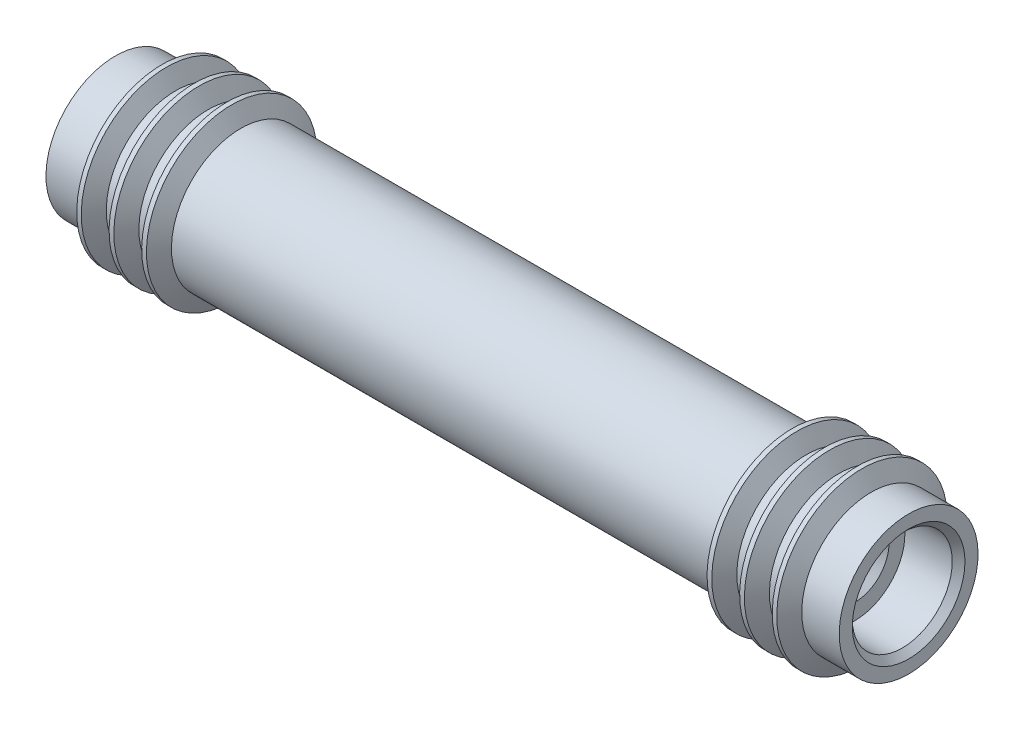
SolidWorks part; units mm, degrees
ref_plane "Front Plane" through (0, 0, 0) normal (0, 0, 1) x (1, 0, 0)
ref_plane "Top Plane" through (0, 0, 0) normal (0, 1, 0) x (1, 0, 0)
ref_plane "Right Plane" through (0, 0, 0) normal (1, 0, 0) x (0, 0, -1)
sketch "Sketch2" plane through (0, 0, 0) normal (0, 0, 1) x (1, 0, 0)
  line L0 (0, 0) -> (0, 28.4375) construction
  line L1 (-31.75, 4) -> (-27.45, 4) construction
  line L2 (-31.75, 4) -> (-31.75, -4) construction
  line L3 (-31.75, -4) -> (-27.45, -4) construction
  line L4 (-27.45, 4) -> (-27.45, -4) construction
  line L5 (-31.75, 4) -> (-27.45, -4) construction
  line L6 (-31.75, -4) -> (-27.45, 4) construction
  line L7 (27.45, 4.5) -> (36.1332, 4.5) construction
  line L8 (27.45, 4.5) -> (27.45, -4.5) construction
  line L9 (27.45, -4.5) -> (36.1332, -4.5) construction
  line L10 (36.1332, 4.5) -> (36.1332, -4.5) construction
  line L11 (27.45, 4.5) -> (36.1332, -4.5) construction
  line L12 (27.45, -4.5) -> (36.1332, 4.5) construction
  line L13 (-31.75, 0) -> (36.1332, 0) construction
  line L14 (-31.75, 5.5562) -> (-28.75, 5.5562)
  line L15 (-28.75, 5.5562) -> (-28.0168, 6.8262)
  line L16 (-28.0168, 6.8262) -> (-27.6572, 6.8262)
  line L19 (-25.4288, 6.8262) -> (-25.0478, 6.8263)
  line L20 (-25.0478, 6.8263) -> (-24.3145, 5.5562)
  line L21 (-20.3302, 3.175) -> (0, 3.175) construction
  line L22 (-31.75, 5.5562) -> (-31.75, 4)
  line L23 (-31.75, 4) -> (-27.45, 4)
  line L24 (-27.45, 4) -> (-27.45, 0)
  line L25 (-27.45, 0) -> (0, 0)
  line L26 (0, 0) -> (0, 3.175)
  line L27 (-33.2419, -5.5563) -> (-33.2419, 5.5562) construction
  line L28 (-26.543, 5.5562) -> (-26.543, 7.68) construction
  line L29 (-26.543, 5.5562) -> (26.543, 5.5562) construction
  line L30 (-31.75, 5.5562) -> (31.75, 5.5562) construction
  line L31 (0, 1.6) -> (-12.5, 1.6) construction
  line L32 (-12.5, 1.6) -> (-14.1, 0) construction
  line L33 (-12.5, 1.6) -> (-12.5, -1.6) construction
  line L34 (-12.5, 1.6) -> (12.5, 1.6) construction
  line L35 (-27.45, 1.7145) -> (-21.925, 1.7145)
  line L36 (-21.925, 1.7145) -> (-21.925, 0)
  line L37 (-27.45, 2.73) -> (-26.942, 2.222)
  line L38 (-21.925, 1.7145) -> (-34.925, 1.7145) construction
  line L39 (-21.925, 1.7145) -> (-21.925, -1.7145) construction
  line L40 (-21.925, -1.7145) -> (-34.925, -1.7145) construction
  line L41 (-34.925, 1.7145) -> (-34.925, -1.7145) construction
  line L42 (-26.942, 2.222) -> (-26.942, 0)
  line L43 (-26.924, 5.5562) -> (-26.162, 5.5562)
  line L44 (-27.6572, 6.8262) -> (-26.924, 5.5562)
  line L45 (-25.4288, 6.8262) -> (-26.162, 5.5562)
  line L46 (-24.3145, 5.5562) -> (-23.5525, 5.5562)
  line L47 (-23.5525, 5.5562) -> (-22.8193, 6.8263)
  line L48 (-22.8193, 6.8263) -> (-22.4383, 6.8263)
  line L49 (-22.4383, 6.8263) -> (-21.7051, 5.5562)
  line L50 (-24.3145, 5.5562) -> (-22.9397, 3.175) construction
  line L51 (-23.9335, 5.5562) -> (-23.9335, 7.9749) construction
  line L52 (-22.9397, 3.175) -> (-20.3302, 3.175) construction
  line L53 (-21.7051, 5.5562) -> (0, 5.5562)
  line L54 (0, 5.5562) -> (0, 3.175)
  line L55 (-21.7051, 5.5562) -> (-20.3302, 3.175) construction
  point P0 (-29.6, 0)
  point P5 (31.7916, 0)
  point P27 (-33.2419, 0)
  point P29 (-12.5, 0)
  point P33 (0, 5.5562)
  point P36 (0, 1.6)
  point P48 (-21.925, 0)
  point P51 (0, 5.5562)
  point P53 (-26.543, 5.5562)
  dimension "D1" = 4.3
  dimension "D4" = 11.1125
  dimension "D5" = 8
  dimension "D6" = 60
  dimension "D7" = 60
  dimension "D8" = 1.27
  dimension "D9" = 60
  dimension "D10" = 53.086
  dimension "D11" = 63.5
  dimension "D12" = 0.381
  dimension "D13" = 45
  dimension "D14" = 25
  dimension "D16" = 3.429
  dimension "D17" = 3.175
  dimension "D18" = 1.27
  dimension "D19" = 0.508
  dimension "D20" = 45
  dimension "D21" = 13
  dimension "D22" = 3
  dimension "D23" = 0.762
  dimension "D24" = 0.381
revolve "Revolve1" add sketch "Sketch2" angle 360 about L13
chamfer "Chamfer1" distance 0.508 angle 45 1 edges at (-31.75, -4, 0)
mirror "Mirror1" about plane through (0, 0, 0) normal (1, 0, 0) of bodies 101
